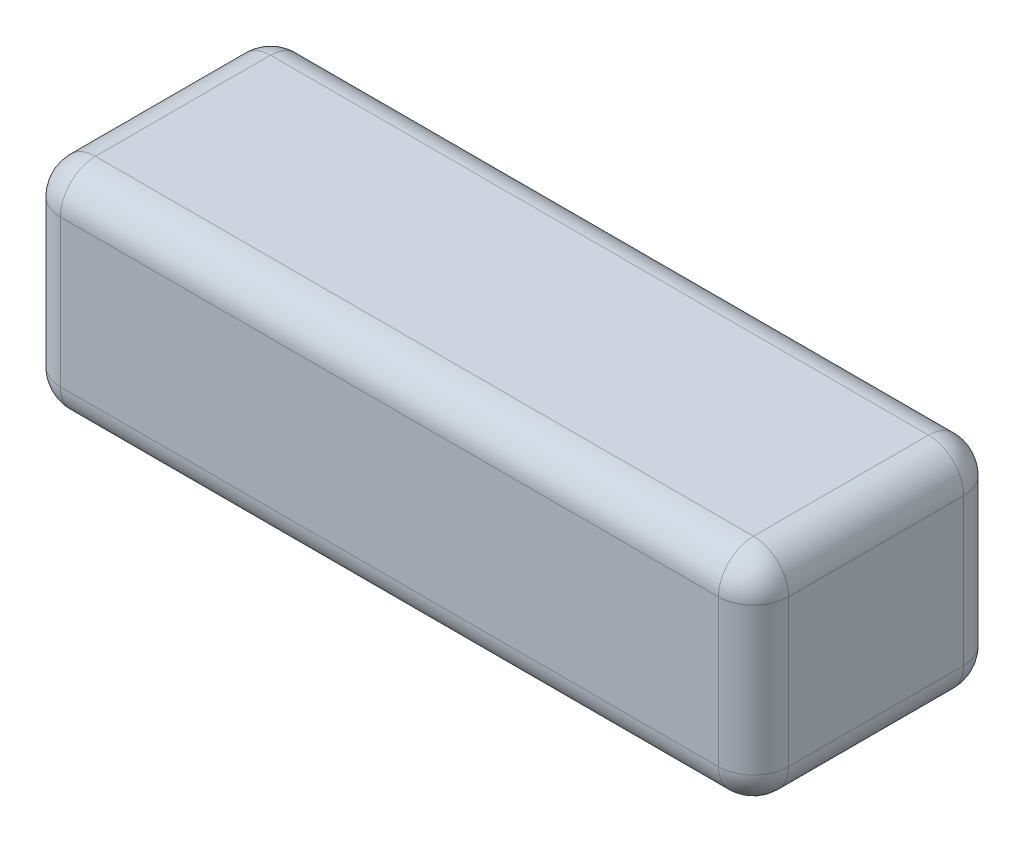
SolidWorks part; units mm, degrees
ref_plane "Front Plane" through (0, 0, 0) normal (0, 0, 1) x (1, 0, 0)
ref_plane "Top Plane" through (0, 0, 0) normal (0, 1, 0) x (1, 0, 0)
ref_plane "Right Plane" through (0, 0, 0) normal (1, 0, 0) x (0, 0, -1)
sketch "Sketch1" plane through (0, 0, 0) normal (0, 1, 0) x (1, 0, 0)
  line L1 (-51.975, 17.5) -> (51.975, 17.5)
  line L2 (-51.975, 17.5) -> (-51.975, -17.5)
  line L3 (-51.975, -17.5) -> (51.975, -17.5)
  line L4 (51.975, 17.5) -> (51.975, -17.5)
  line L5 (-51.975, 17.5) -> (51.975, -17.5) construction
  line L6 (-51.975, -17.5) -> (51.975, 17.5) construction
  point P0 (0, 0)
  dimension "D1" = 35
  dimension "D2" = 103.95
extrude "Boss-Extrude1" add sketch "Sketch1" along normal blind 31
fillet "Fillet1" radius 5 12 edges at (-51.975, 0, 0) (51.975, 0, 0) (51.975, 15.5, -17.5) (-51.975, 15.5, -17.5) (0, 0, -17.5) (-51.975, 15.5, 17.5) (51.975, 15.5, 17.5) (0, 0, 17.5) (0, 31, 17.5) (-51.975, 31, 0) (0, 31, -17.5) (51.975, 31, 0)
